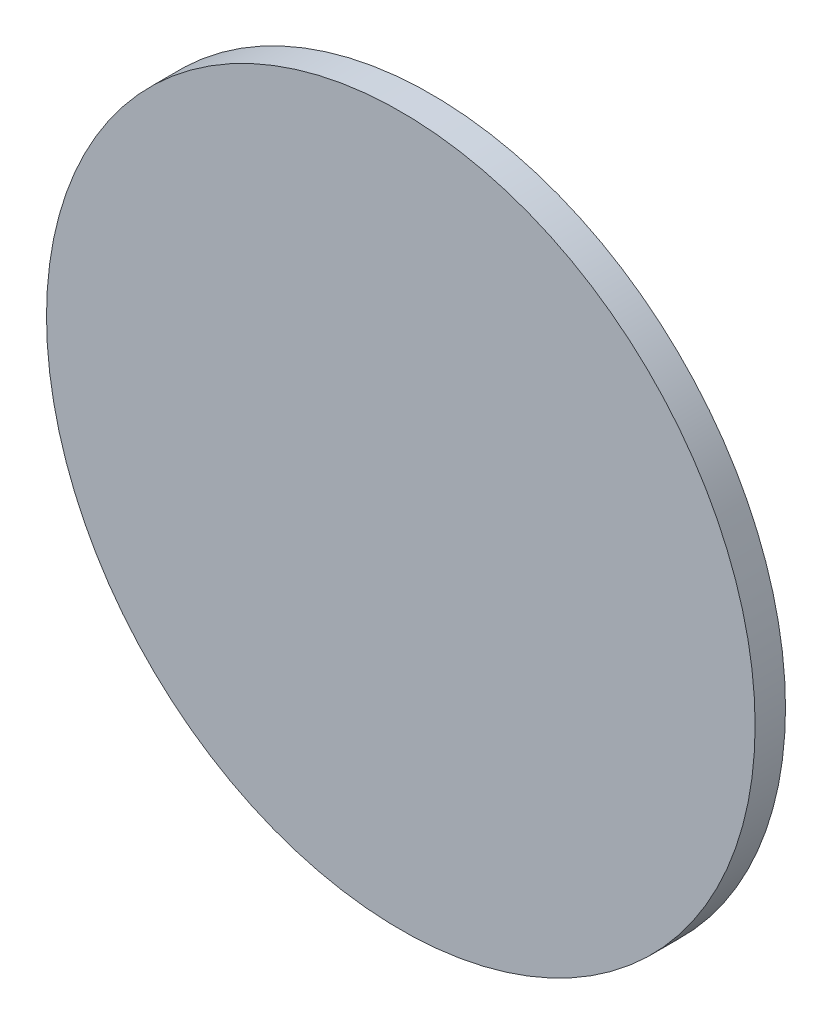
SolidWorks part; units mm, degrees
ref_plane "Front Plane" through (0, 0, 0) normal (0, 0, 1) x (1, 0, 0)
ref_plane "Top Plane" through (0, 0, 0) normal (0, 1, 0) x (1, 0, 0)
ref_plane "Right Plane" through (0, 0, 0) normal (1, 0, 0) x (0, 0, -1)
sketch "Sketch1" plane through (0, 0, 0) normal (0, 0, 1) x (1, 0, 0)
  circle A0 centre (0, 0) radius 44.45
  dimension "D1" = 88.9
extrude "Boss-Extrude1" add sketch "Sketch1" along normal blind 3.81
equation "\"D1@Boss-Extrude1\"=0.15"
